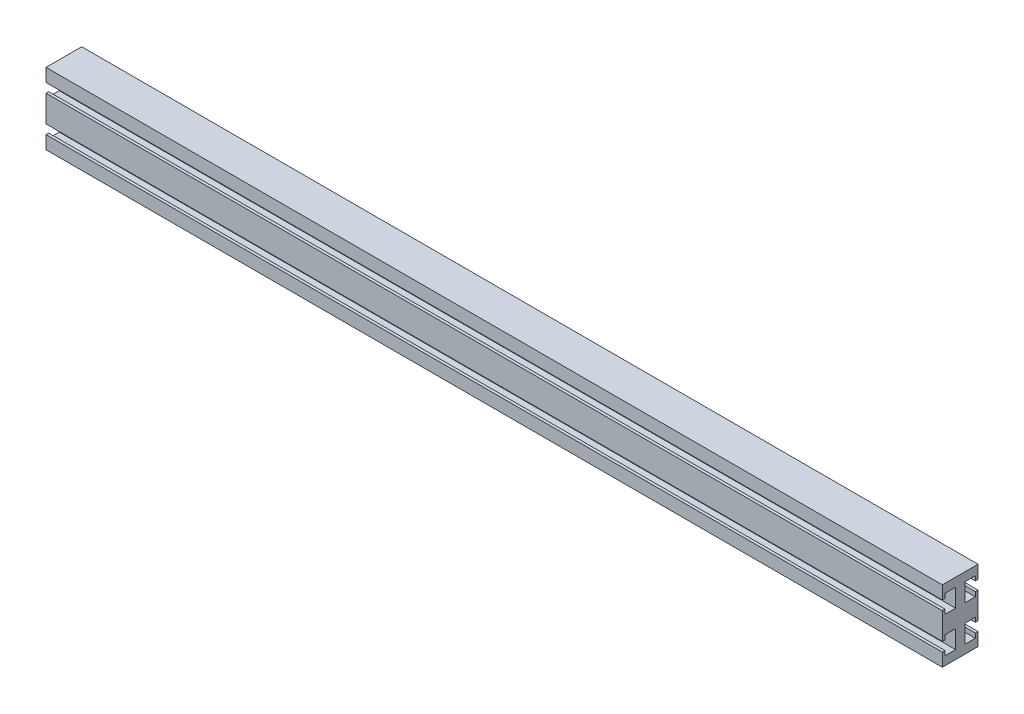
SolidWorks part; units mm, degrees
ref_plane "Front Plane" through (0, 0, 0) normal (0, 0, 1) x (1, 0, 0)
ref_plane "Top Plane" through (0, 0, 0) normal (0, 1, 0) x (1, 0, 0)
ref_plane "Right Plane" through (0, 0, 0) normal (1, 0, 0) x (0, 0, -1)
sketch "Sketch1" plane through (0, 0, 0) normal (0, 1, 0) x (1, 0, 0)
  line L1 (-250, -9.95) -> (250, -9.95)
  line L2 (-250, -9.95) -> (-250, 9.95)
  line L3 (-250, 9.95) -> (250, 9.95)
  line L4 (250, -9.95) -> (250, 9.95)
  line L5 (-250, -9.95) -> (250, 9.95) construction
  line L6 (-250, 9.95) -> (250, -9.95) construction
  point P0 (0, 0)
  dimension "D1" = 19.9
  dimension "D2" = 500
extrude "Boss-Extrude1" add sketch "Sketch1" along normal mid plane 39.82
sketch "Sketch2" plane through (250, 0, 0) normal (1, 0, 0) x (0, 0, -1)
  line L0 (-9.95, 19.91) -> (9.95, 19.91) construction
  line L1 (-9.95, 19.91) -> (-9.95, -19.91) construction
  line L2 (0, 0) -> (0, 43.7862) construction
  line L3 (-9.95, 7.42) -> (-8.45, 7.42)
  line L4 (-8.45, 7.42) -> (-8.45, 4.92)
  line L5 (-8.45, 4.92) -> (-2.56, 4.92)
  line L6 (-2.56, 4.92) -> (-2.56, 15.09)
  line L7 (-2.56, 15.09) -> (-8.45, 15.09)
  line L8 (-8.45, 15.09) -> (-8.45, 12.59)
  line L9 (-8.45, 12.59) -> (-9.95, 12.59)
  line L10 (-9.95, 7.42) -> (-9.95, 12.59)
  dimension "D1" = 7.32
  dimension "D2" = 2.5
  dimension "D3" = 5.17
  dimension "D4" = 1.5
  dimension "D5" = 7.39
extrude "Cut-Extrude1" cut sketch "Sketch2" against normal through all
mirror "Mirror1" about plane through (0, 0, 0) normal (0, 0, 1) of "Cut-Extrude1"
mirror "Mirror2" about plane through (0, 0, 0) normal (0, 1, 0) of "Mirror1", "Cut-Extrude1"
